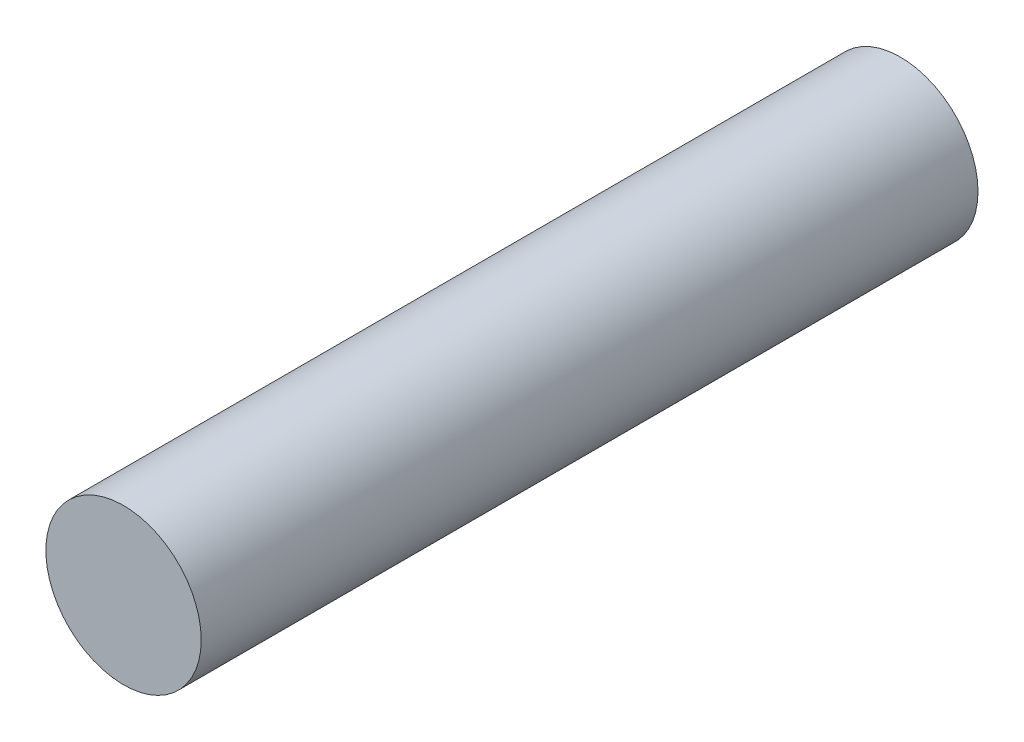
SolidWorks part; units mm, degrees
ref_plane "前视基准面" through (0, 0, 0) normal (0, 0, 1) x (1, 0, 0)
ref_plane "上视基准面" through (0, 0, 0) normal (0, 1, 0) x (1, 0, 0)
ref_plane "右视基准面" through (0, 0, 0) normal (1, 0, 0) x (0, 0, -1)
sketch "草图1" plane through (0, 0, 0) normal (0, 0, 1) x (1, 0, 0)
  circle A0 centre (0, 0) radius 1.8
extrude "凸台-拉伸1" add sketch "草图1" along normal blind 18 contours A0
